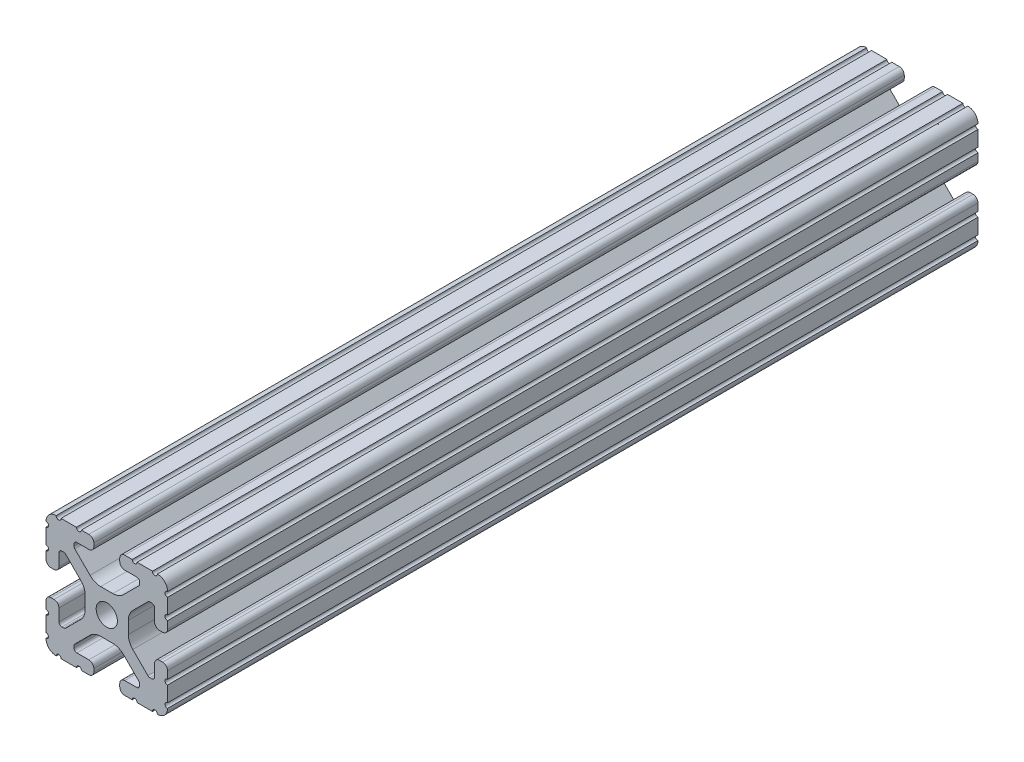
SolidWorks part; units mm, degrees
material "6061 Alloy"
ref_plane "Front Plane" through (0, 0, 0) normal (0, 0, 1) x (1, 0, 0)
ref_plane "Top Plane" through (0, 0, 0) normal (0, 1, 0) x (1, 0, 0)
ref_plane "Right Plane" through (0, 0, 0) normal (1, 0, 0) x (0, 0, -1)
sketch "Sketch1" plane through (0, 0, 0) normal (0, 0, 1) x (1, 0, 0)
  line L0 (0, 25.6181) -> (0, -24.623) construction
  line L1 (-20.8943, 0) -> (20.4607, 0) construction
  line L2 (-10.0229, 12.9148) -> (-5.2522, 8.144)
  line L3 (-10.287, 14.0843) -> (-10.287, 13.5524)
  line L4 (-5.6176, 14.986) -> (-9.3853, 14.986)
  line L5 (-4.064, 17.4964) -> (-4.064, 16.5396)
  line L6 (-7.9742, 19.05) -> (-5.6176, 19.05)
  line L7 (-14.3277, 19.05) -> (-9.4982, 19.05)
  line L8 (-19.05, 9.4961) -> (-19.05, 14.3277)
  line L9 (-19.05, 5.6176) -> (-19.05, 7.9763)
  line L10 (-16.5396, 4.064) -> (-17.4964, 4.064)
  line L11 (-14.986, 9.3853) -> (-14.986, 5.6176)
  line L12 (-13.516, 10.287) -> (-14.0843, 10.287)
  line L13 (-8.1476, 5.2921) -> (-12.8784, 10.0229)
  line L14 (-6.7564, -1.9335) -> (-6.7564, 1.9335)
  line L15 (-12.8784, -10.0229) -> (-8.1476, -5.2921)
  line L16 (-14.0843, -10.287) -> (-13.516, -10.287)
  line L17 (-14.986, -5.6176) -> (-14.986, -9.3853)
  line L18 (-17.4964, -4.064) -> (-16.5396, -4.064)
  line L19 (-19.05, -7.9763) -> (-19.05, -5.6176)
  line L20 (-19.05, -14.3277) -> (-19.05, -9.4961)
  line L21 (-9.4961, -19.05) -> (-14.3277, -19.05)
  line L22 (-5.6176, -19.05) -> (-7.9763, -19.05)
  line L23 (-4.064, -17.4964) -> (-4.064, -16.5396)
  line L24 (10.0229, -12.9148) -> (5.2522, -8.144)
  line L25 (10.287, -14.0843) -> (10.287, -13.5524)
  line L26 (5.6176, -14.986) -> (9.3853, -14.986)
  line L28 (-1.9022, 6.7564) -> (1.9022, 6.7564)
  line L29 (-1.9022, -6.7564) -> (1.9022, -6.7564)
  line L31 (-5.6176, -14.986) -> (-9.3853, -14.986)
  line L32 (-10.287, -14.0843) -> (-10.287, -13.5524)
  line L33 (-10.0229, -12.9148) -> (-5.2522, -8.144)
  line L66 (4.064, -16.5396) -> (4.064, -17.4964)
  line L67 (5.6176, -19.05) -> (7.9763, -19.05)
  line L68 (9.4961, -19.05) -> (14.3277, -19.05)
  line L69 (19.05, -14.3277) -> (19.05, -9.4961)
  line L70 (19.05, -7.9763) -> (19.05, -5.6176)
  line L71 (17.4964, -4.064) -> (16.5396, -4.064)
  line L72 (14.986, -5.6176) -> (14.986, -9.3853)
  line L73 (14.0843, -10.287) -> (13.516, -10.287)
  line L74 (12.8784, -10.0229) -> (8.1476, -5.2921)
  line L75 (6.7564, -1.9335) -> (6.7564, 1.9335)
  line L76 (8.1476, 5.2921) -> (12.8784, 10.0229)
  line L77 (13.516, 10.287) -> (14.0843, 10.287)
  line L78 (14.986, 9.3853) -> (14.986, 5.6176)
  line L79 (16.5396, 4.064) -> (17.4964, 4.064)
  line L80 (19.05, 5.6176) -> (19.05, 7.9763)
  line L81 (19.05, 9.4961) -> (19.05, 14.3277)
  line L82 (14.3277, 19.05) -> (9.4982, 19.05)
  line L83 (7.9742, 19.05) -> (5.6176, 19.05)
  line L84 (4.064, 17.4964) -> (4.064, 16.5396)
  line L85 (5.6176, 14.986) -> (9.3853, 14.986)
  line L86 (10.287, 14.0843) -> (10.287, 13.5524)
  line L87 (10.0229, 12.9148) -> (5.2522, 8.144)
  arc A0 (-10.0229, 12.9148) -> (-10.287, 13.5524) centre (-9.3853, 13.5524) cw
  circle A1 centre (0, 0) radius 3.3274
  arc A2 (-10.287, 14.0843) -> (-9.3853, 14.986) centre (-9.3853, 14.0843) cw
  arc A3 (-4.064, 16.5396) -> (-5.6176, 14.986) centre (-5.6176, 16.5396) cw
  arc A4 (-5.6176, 19.05) -> (-4.064, 17.4964) centre (-5.6176, 17.4964) cw
  arc A5 (-7.9742, 19.05) -> (-9.4982, 19.05) centre (-8.7362, 19.05) cw
  arc A6 (-14.3277, 19.05) -> (-15.8475, 19.05) centre (-15.0876, 18.9933) cw
  arc A7 (-19.05, 15.8475) -> (-15.8475, 19.05) centre (-15.8751, 15.8751) cw
  arc A8 (-19.05, 15.8475) -> (-19.05, 14.3277) centre (-18.9933, 15.0876) cw
  arc A9 (-19.05, 9.4961) -> (-19.05, 7.9763) centre (-18.9933, 8.7362) cw
  arc A10 (-17.4964, 4.064) -> (-19.05, 5.6176) centre (-17.4964, 5.6176) cw
  arc A11 (-14.986, 5.6176) -> (-16.5396, 4.064) centre (-16.5396, 5.6176) cw
  arc A12 (-14.986, 9.3853) -> (-14.0843, 10.287) centre (-14.0843, 9.3853) cw
  arc A13 (-13.516, 10.287) -> (-12.8784, 10.0229) centre (-13.516, 9.3853) cw
  arc A14 (-8.1476, 5.2921) -> (-6.7564, 1.9335) centre (-11.5062, 1.9335) cw
  arc A15 (-6.7564, -1.9335) -> (-8.1476, -5.2921) centre (-11.5062, -1.9335) cw
  arc A16 (-12.8784, -10.0229) -> (-13.516, -10.287) centre (-13.516, -9.3853) cw
  arc A17 (-14.0843, -10.287) -> (-14.986, -9.3853) centre (-14.0843, -9.3853) cw
  arc A18 (-16.5396, -4.064) -> (-14.986, -5.6176) centre (-16.5396, -5.6176) cw
  arc A19 (-19.05, -5.6176) -> (-17.4964, -4.064) centre (-17.4964, -5.6176) cw
  arc A20 (-19.05, -7.9763) -> (-19.05, -9.4961) centre (-18.9933, -8.7362) cw
  arc A21 (-19.05, -14.3277) -> (-19.05, -15.8475) centre (-18.9933, -15.0876) cw
  arc A22 (-15.8475, -19.05) -> (-19.05, -15.8475) centre (-15.8751, -15.8751) cw
  arc A23 (-15.8475, -19.05) -> (-14.3277, -19.05) centre (-15.0876, -18.9933) cw
  arc A24 (-9.4961, -19.05) -> (-7.9763, -19.05) centre (-8.7362, -18.9933) cw
  arc A25 (-4.064, -17.4964) -> (-5.6176, -19.05) centre (-5.6176, -17.4964) cw
  arc A26 (-5.2522, -8.144) -> (-1.9022, -6.7564) centre (-1.9022, -11.494) cw
  arc A27 (1.9022, -6.7564) -> (5.2522, -8.144) centre (1.9022, -11.494) cw
  arc A28 (10.0229, -12.9148) -> (10.287, -13.5524) centre (9.3853, -13.5524) cw
  arc A29 (10.287, -14.0843) -> (9.3853, -14.986) centre (9.3853, -14.0843) cw
  arc A30 (4.064, -16.5396) -> (5.6176, -14.986) centre (5.6176, -16.5396) cw
  arc A31 (-4.064, -16.5396) -> (-5.6176, -14.986) centre (-5.6176, -16.5396) ccw
  arc A32 (-10.287, -14.0843) -> (-9.3853, -14.986) centre (-9.3853, -14.0843) ccw
  arc A33 (-10.0229, -12.9148) -> (-10.287, -13.5524) centre (-9.3853, -13.5524) ccw
  arc A79 (4.064, -17.4964) -> (5.6176, -19.05) centre (5.6176, -17.4964) ccw
  arc A80 (9.4961, -19.05) -> (7.9763, -19.05) centre (8.7362, -18.9933) ccw
  arc A81 (15.8475, -19.05) -> (14.3277, -19.05) centre (15.0876, -18.9933) ccw
  arc A82 (15.8475, -19.05) -> (19.05, -15.8475) centre (15.8751, -15.8751) ccw
  arc A83 (19.05, -14.3277) -> (19.05, -15.8475) centre (18.9933, -15.0876) ccw
  arc A84 (19.05, -7.9763) -> (19.05, -9.4961) centre (18.9933, -8.7362) ccw
  arc A85 (19.05, -5.6176) -> (17.4964, -4.064) centre (17.4964, -5.6176) ccw
  arc A86 (16.5396, -4.064) -> (14.986, -5.6176) centre (16.5396, -5.6176) ccw
  arc A87 (14.0843, -10.287) -> (14.986, -9.3853) centre (14.0843, -9.3853) ccw
  arc A88 (12.8784, -10.0229) -> (13.516, -10.287) centre (13.516, -9.3853) ccw
  arc A89 (6.7564, -1.9335) -> (8.1476, -5.2921) centre (11.5062, -1.9335) ccw
  arc A90 (8.1476, 5.2921) -> (6.7564, 1.9335) centre (11.5062, 1.9335) ccw
  arc A91 (13.516, 10.287) -> (12.8784, 10.0229) centre (13.516, 9.3853) ccw
  arc A92 (14.986, 9.3853) -> (14.0843, 10.287) centre (14.0843, 9.3853) ccw
  arc A93 (14.986, 5.6176) -> (16.5396, 4.064) centre (16.5396, 5.6176) ccw
  arc A94 (17.4964, 4.064) -> (19.05, 5.6176) centre (17.4964, 5.6176) ccw
  arc A95 (19.05, 9.4961) -> (19.05, 7.9763) centre (18.9933, 8.7362) ccw
  arc A96 (19.05, 15.8475) -> (19.05, 14.3277) centre (18.9933, 15.0876) ccw
  arc A97 (19.05, 15.8475) -> (15.8475, 19.05) centre (15.8751, 15.8751) ccw
  arc A98 (14.3277, 19.05) -> (15.8475, 19.05) centre (15.0876, 18.9933) ccw
  arc A99 (7.9742, 19.05) -> (9.4982, 19.05) centre (8.7362, 19.05) ccw
  arc A100 (5.6176, 19.05) -> (4.064, 17.4964) centre (5.6176, 17.4964) ccw
  arc A101 (4.064, 16.5396) -> (5.6176, 14.986) centre (5.6176, 16.5396) ccw
  arc A102 (10.287, 14.0843) -> (9.3853, 14.986) centre (9.3853, 14.0843) ccw
  arc A103 (10.0229, 12.9148) -> (10.287, 13.5524) centre (9.3853, 13.5524) ccw
  arc A104 (1.9022, 6.7564) -> (5.2522, 8.144) centre (1.9022, 11.494) ccw
  arc A105 (-5.2522, 8.144) -> (-1.9022, 6.7564) centre (-1.9022, 11.494) ccw
  dimension "D1" = 6.6548
  dimension "D2" = 19.05
  dimension "D3" = 38.1
  dimension "D4" = 20.574
  dimension "D5" = 13.5128
  dimension "D6" = 4.064
  dimension "D7" = 8.128
  dimension "D8" = 4.064
  dimension "D9" = 12.2936
extrude "Extrude1" add sketch "Sketch1" against normal blind 254
